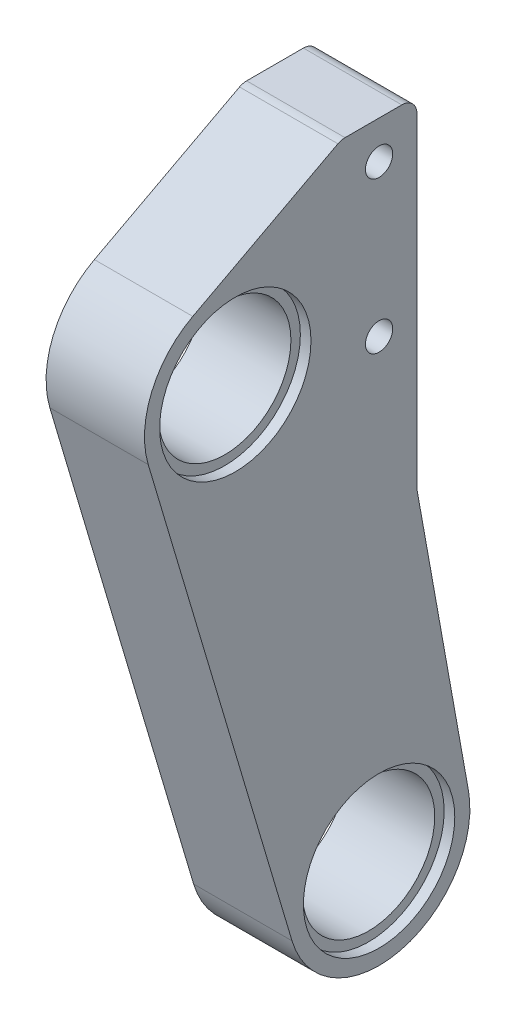
SolidWorks part; units mm, degrees
ref_plane "Front Plane" through (0, 0, 0) normal (0, 0, 1) x (1, 0, 0)
ref_plane "Top Plane" through (0, 0, 0) normal (0, 1, 0) x (1, 0, 0)
ref_plane "Right Plane" through (0, 0, 0) normal (1, 0, 0) x (0, 0, -1)
sketch "Sketch1" plane through (0, 0, 0) normal (1, 0, 0) x (0, 0, -1)
  line L0 (-38.7398, 0.7427) -> (-14.6098, -80.5373)
  line L3 (-6.35, 31.75) -> (6.35, 31.75)
  line L4 (6.35, -25.4) -> (6.35, 31.75)
  line L7 (14.9994, -73.5029) -> (6.35, -25.4)
  line L8 (-6.35, 31.75) -> (-31.2661, 18.546)
  circle A0 centre (0, 0) radius 2.286
  circle A1 centre (0, 25.4) radius 2.286
  circle A2 centre (0, -76.2) radius 11.1125
  arc A3 (-14.6098, -80.5373) -> (14.9994, -73.5029) centre (0, -76.2) ccw
  circle A4 centre (-24.13, 5.08) radius 11.1125
  arc A5 (-31.2661, 18.546) -> (-38.7398, 0.7427) centre (-24.13, 5.08) ccw
  circle A6 centre (0, -76.2) radius 11.1125 construction
  point P5 (0, 0)
  point P7 (0, 0)
  point P10 (0, 31.75)
  dimension "D1" = 12.7
  dimension "D5" = 4.572
  dimension "D6" = 22.225
  dimension "D7" = 15.24
  dimension "D9" = 22.225
  dimension "D2" = 25.4
  dimension "D3" = 6.35
  dimension "D4" = 57.15
extrude "Boss-Extrude1" add sketch "Sketch1" along normal blind 16.51
sketch "Sketch2" plane through (16.51, 0, 0) normal (1, 0, 0) x (0, 0, -1)
  circle A0 centre (0, -76.2) radius 12.7
  circle A1 centre (-24.13, 5.08) radius 12.7
  dimension "D1" = 25.4
extrude "Cut-Extrude1" cut sketch "Sketch2" against normal blind 1.778
fillet "Fillet1" radius 2.54 3 edges at (8.255, -25.4, -6.35) (8.255, 31.75, 6.35) (8.255, 31.75, -6.35)
